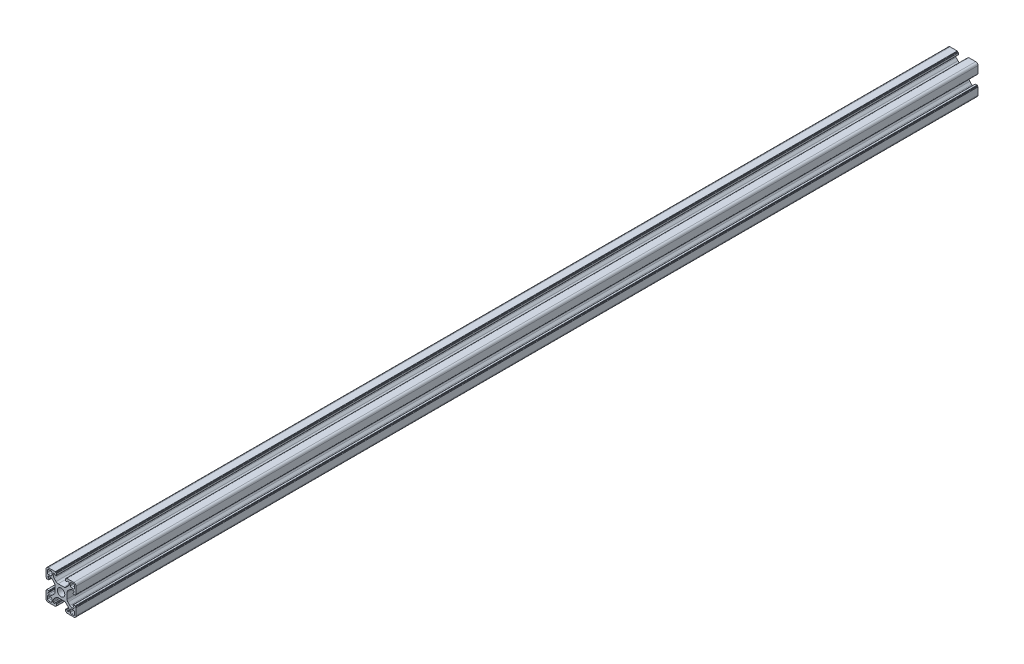
SolidWorks part; units mm, degrees
material "1060 Сплав"
ref_plane "Спереди" through (0, 0, 0) normal (0, 0, 1) x (1, 0, 0)
ref_plane "Сверху" through (0, 0, 0) normal (0, 1, 0) x (1, 0, 0)
ref_plane "Справа" through (0, 0, 0) normal (1, 0, 0) x (0, 0, -1)
sketch "Эскиз1" plane through (0, 0, 0) normal (0, 0, 1) x (1, 0, 0)
  line L0 (-22.0052, 70.3096) -> (-25.0052, 67.3096) construction
  line L1 (-31.1052, 65.2096) -> (-29.2064, 65.2096)
  line L2 (-31.1052, 61.2096) -> (-21.1052, 71.2096) construction
  line L3 (-23.5052, 68.8096) -> (-25.0052, 70.3096) construction
  line L4 (-27.7922, 65.7954) -> (-26.4909, 67.0967)
  line L5 (-24.2052, 67.3096) -> (-22.8052, 67.3096)
  line L6 (-25.0052, 68.1096) -> (-25.0052, 69.5096)
  line L7 (-22.8052, 70.3096) -> (-24.2052, 70.3096)
  line L8 (-25.9052, 69.4096) -> (-25.9052, 68.5109)
  line L9 (-27.3419, 69.2829) -> (-26.8616, 69.7632)
  line L10 (-27.9052, 70.7587) -> (-27.4052, 70.7587)
  line L11 (-27.5187, 69.2096) -> (-27.8052, 69.2096)
  line L12 (-26.508, 69.9096) -> (-26.4052, 69.9096)
  line L13 (-27.4052, 71.0596) -> (-27.4052, 70.7587)
  line L14 (-28.0552, 70.6087) -> (-28.0552, 69.4596)
  line L15 (-22.6052, 71.2096) -> (-27.2552, 71.2096)
  line L16 (-22.0052, 69.5096) -> (-22.0052, 68.1096)
  line L17 (-21.1052, 69.7096) -> (-21.1052, 65.0596)
  line L18 (-21.7061, 64.2596) -> (-22.8552, 64.2596)
  line L19 (-21.2552, 64.9096) -> (-21.5561, 64.9096)
  line L20 (-22.4052, 65.8068) -> (-22.4052, 65.9096)
  line L21 (-23.1052, 64.7961) -> (-23.1052, 64.5096)
  line L22 (-21.5561, 64.4096) -> (-21.5561, 64.9096)
  line L23 (-23.0319, 64.9729) -> (-22.5516, 65.4532)
  line L24 (-22.9052, 66.4096) -> (-23.8039, 66.4096)
  line L25 (-26.5194, 64.5226) -> (-25.2181, 65.8239)
  line L26 (-27.1052, 61.2096) -> (-27.1052, 63.1084)
  line L27 (-27.1052, 61.2096) -> (-27.1052, 59.3109)
  line L28 (-26.5194, 57.8967) -> (-25.2181, 56.5954)
  line L29 (-25.0052, 54.3096) -> (-25.0052, 52.9096)
  line L30 (-24.2052, 55.1096) -> (-22.8052, 55.1096)
  line L31 (-22.0052, 52.9096) -> (-22.0052, 54.3096)
  line L32 (-22.9052, 56.0096) -> (-23.8039, 56.0096)
  line L33 (-23.0319, 57.4464) -> (-22.5516, 56.9661)
  line L34 (-21.5561, 58.0096) -> (-21.5561, 57.5096)
  line L35 (-23.1052, 57.6232) -> (-23.1052, 57.9096)
  line L36 (-22.4052, 56.6125) -> (-22.4052, 56.5096)
  line L37 (-21.2552, 57.5096) -> (-21.5561, 57.5096)
  line L38 (-21.7061, 58.1596) -> (-22.8552, 58.1596)
  line L39 (-21.1052, 52.7096) -> (-21.1052, 57.3596)
  line L40 (-22.8052, 52.1096) -> (-24.2052, 52.1096)
  line L41 (-22.6052, 51.2096) -> (-27.2552, 51.2096)
  line L42 (-28.0552, 51.8106) -> (-28.0552, 52.9596)
  line L43 (-27.4052, 51.3596) -> (-27.4052, 51.6606)
  line L44 (-26.508, 52.5096) -> (-26.4052, 52.5096)
  line L45 (-27.5187, 53.2096) -> (-27.8052, 53.2096)
  line L46 (-27.9052, 51.6606) -> (-27.4052, 51.6606)
  line L47 (-27.3419, 53.1364) -> (-26.8616, 52.6561)
  line L48 (-25.9052, 53.0096) -> (-25.9052, 53.9084)
  line L49 (-27.7922, 56.6239) -> (-26.4909, 55.3226)
  line L50 (-31.1052, 57.2096) -> (-29.2064, 57.2096)
  line L51 (-22.0052, 52.1096) -> (-25.0052, 55.1096) construction
  line L52 (-31.1052, 61.2096) -> (-21.1052, 51.2096) construction
  line L53 (-23.5052, 53.6096) -> (-22.0052, 55.1096) construction
  line L54 (-31.1052, 57.2096) -> (-33.0039, 57.2096)
  line L55 (-34.4181, 56.6239) -> (-35.7194, 55.3226)
  line L56 (-38.0052, 55.1096) -> (-39.4052, 55.1096)
  line L57 (-37.2052, 54.3096) -> (-37.2052, 52.9096)
  line L58 (-39.4052, 52.1096) -> (-38.0052, 52.1096)
  line L59 (-36.3052, 53.0096) -> (-36.3052, 53.9084)
  line L60 (-34.8684, 53.1364) -> (-35.3487, 52.6561)
  line L61 (-34.3052, 51.6606) -> (-34.8052, 51.6606)
  line L62 (-34.6916, 53.2096) -> (-34.4052, 53.2096)
  line L63 (-35.7023, 52.5096) -> (-35.8052, 52.5096)
  line L64 (-34.8052, 51.3596) -> (-34.8052, 51.6606)
  line L65 (-34.1552, 51.8106) -> (-34.1552, 52.9596)
  line L66 (-39.6052, 51.2096) -> (-34.9552, 51.2096)
  line L67 (-40.2052, 52.9096) -> (-40.2052, 54.3096)
  line L68 (-41.1052, 52.7096) -> (-41.1052, 57.3596)
  line L69 (-40.5042, 58.1596) -> (-39.3552, 58.1596)
  line L70 (-40.9552, 57.5096) -> (-40.6542, 57.5096)
  line L71 (-39.8052, 56.6125) -> (-39.8052, 56.5096)
  line L72 (-39.1052, 57.6232) -> (-39.1052, 57.9096)
  line L73 (-40.6542, 58.0096) -> (-40.6542, 57.5096)
  line L74 (-39.1784, 57.4464) -> (-39.6587, 56.9661)
  line L75 (-39.3052, 56.0096) -> (-38.4064, 56.0096)
  line L76 (-35.6909, 57.8967) -> (-36.9922, 56.5954)
  line L77 (-35.1052, 61.2096) -> (-35.1052, 59.3109)
  line L78 (-40.2052, 52.1096) -> (-37.2052, 55.1096) construction
  line L79 (-31.1052, 61.2096) -> (-41.1052, 51.2096) construction
  line L80 (-38.7052, 53.6096) -> (-37.2052, 52.1096) construction
  line L81 (-35.1052, 61.2096) -> (-35.1052, 63.1084)
  line L82 (-35.6909, 64.5226) -> (-36.9922, 65.8239)
  line L83 (-37.2052, 68.1096) -> (-37.2052, 69.5096)
  line L84 (-38.0052, 67.3096) -> (-39.4052, 67.3096)
  line L85 (-40.2052, 69.5096) -> (-40.2052, 68.1096)
  line L86 (-39.3052, 66.4096) -> (-38.4064, 66.4096)
  line L87 (-39.1784, 64.9729) -> (-39.6587, 65.4532)
  line L88 (-40.6542, 64.4096) -> (-40.6542, 64.9096)
  line L89 (-39.1052, 64.7961) -> (-39.1052, 64.5096)
  line L90 (-39.8052, 65.8068) -> (-39.8052, 65.9096)
  line L91 (-40.9552, 64.9096) -> (-40.6542, 64.9096)
  line L92 (-40.5042, 64.2596) -> (-39.3552, 64.2596)
  line L93 (-41.1052, 69.7096) -> (-41.1052, 65.0596)
  line L94 (-39.4052, 70.3096) -> (-38.0052, 70.3096)
  line L95 (-39.6052, 71.2096) -> (-34.9552, 71.2096)
  line L96 (-34.1552, 70.6087) -> (-34.1552, 69.4596)
  line L97 (-34.8052, 71.0596) -> (-34.8052, 70.7587)
  line L98 (-35.7023, 69.9096) -> (-35.8052, 69.9096)
  line L99 (-34.6916, 69.2096) -> (-34.4052, 69.2096)
  line L100 (-34.3052, 70.7587) -> (-34.8052, 70.7587)
  line L101 (-34.8684, 69.2829) -> (-35.3487, 69.7632)
  line L102 (-36.3052, 69.4096) -> (-36.3052, 68.5109)
  line L103 (-34.4181, 65.7954) -> (-35.7194, 67.0967)
  line L104 (-31.1052, 65.2096) -> (-33.0039, 65.2096)
  line L105 (-42.8692, 61.2096) -> (-19.6008, 61.2096) construction
  line L106 (-40.2052, 70.3096) -> (-37.2052, 67.3096) construction
  line L107 (-31.1052, 49.1232) -> (-31.1052, 71.9286) construction
  line L108 (-31.1052, 61.2096) -> (-41.1052, 71.2096) construction
  line L109 (-38.7052, 68.8096) -> (-40.2052, 67.3096) construction
  arc A0 (-22.0052, 69.5096) -> (-22.8052, 70.3096) centre (-22.8052, 69.5096) ccw
  arc A1 (-24.2052, 70.3096) -> (-25.0052, 69.5096) centre (-24.2052, 69.5096) ccw
  arc A2 (-24.2052, 67.3096) -> (-25.0052, 68.1096) centre (-24.2052, 68.1096) cw
  arc A3 (-22.6052, 71.2096) -> (-21.1052, 69.7096) centre (-22.6052, 69.7096) cw
  arc A4 (-27.9052, 70.7587) -> (-28.0552, 70.6087) centre (-27.9052, 70.6087) ccw
  arc A5 (-27.2552, 71.2096) -> (-27.4052, 71.0596) centre (-27.2552, 71.0596) ccw
  arc A6 (-27.5187, 69.2096) -> (-27.3419, 69.2829) centre (-27.5187, 69.4596) ccw
  arc A7 (-27.8052, 69.2096) -> (-28.0552, 69.4596) centre (-27.8052, 69.4596) cw
  arc A8 (-26.8616, 69.7632) -> (-26.508, 69.9096) centre (-26.508, 69.4096) cw
  arc A9 (-26.4052, 69.9096) -> (-25.9052, 69.4096) centre (-26.4052, 69.4096) cw
  arc A10 (-28.6052, 61.2096) -> (-31.1052, 63.7096) centre (-31.1052, 61.2096) ccw
  arc A11 (-29.2064, 65.2096) -> (-27.7922, 65.7954) centre (-29.2064, 67.2096) ccw
  arc A12 (-25.9052, 68.5109) -> (-26.4909, 67.0967) centre (-27.9052, 68.5109) cw
  arc A13 (-22.0052, 68.1096) -> (-22.8052, 67.3096) centre (-22.8052, 68.1096) cw
  arc A14 (-22.4052, 65.9096) -> (-22.9052, 66.4096) centre (-22.9052, 65.9096) ccw
  arc A15 (-22.5516, 65.4532) -> (-22.4052, 65.8068) centre (-22.9052, 65.8068) ccw
  arc A16 (-23.1052, 64.5096) -> (-22.8552, 64.2596) centre (-22.8552, 64.5096) ccw
  arc A17 (-23.1052, 64.7961) -> (-23.0319, 64.9729) centre (-22.8552, 64.7961) cw
  arc A18 (-21.1052, 65.0596) -> (-21.2552, 64.9096) centre (-21.2552, 65.0596) cw
  arc A19 (-21.5561, 64.4096) -> (-21.7061, 64.2596) centre (-21.7061, 64.4096) cw
  arc A20 (-23.8039, 66.4096) -> (-25.2181, 65.8239) centre (-23.8039, 64.4096) ccw
  arc A21 (-27.1052, 63.1084) -> (-26.5194, 64.5226) centre (-25.1052, 63.1084) cw
  arc A22 (-22.8052, 52.1096) -> (-22.0052, 52.9096) centre (-22.8052, 52.9096) ccw
  arc A23 (-22.0052, 54.3096) -> (-22.8052, 55.1096) centre (-22.8052, 54.3096) ccw
  arc A24 (-25.0052, 54.3096) -> (-24.2052, 55.1096) centre (-24.2052, 54.3096) cw
  arc A25 (-21.1052, 52.7096) -> (-22.6052, 51.2096) centre (-22.6052, 52.7096) cw
  arc A26 (-21.5561, 58.0096) -> (-21.7061, 58.1596) centre (-21.7061, 58.0096) ccw
  arc A27 (-21.1052, 57.3596) -> (-21.2552, 57.5096) centre (-21.2552, 57.3596) ccw
  arc A28 (-23.1052, 57.6232) -> (-23.0319, 57.4464) centre (-22.8552, 57.6232) ccw
  arc A29 (-23.1052, 57.9096) -> (-22.8552, 58.1596) centre (-22.8552, 57.9096) cw
  arc A30 (-22.5516, 56.9661) -> (-22.4052, 56.6125) centre (-22.9052, 56.6125) cw
  arc A31 (-22.4052, 56.5096) -> (-22.9052, 56.0096) centre (-22.9052, 56.5096) cw
  arc A32 (-31.1052, 58.7096) -> (-28.6052, 61.2096) centre (-31.1052, 61.2096) ccw
  arc A33 (-27.1052, 59.3109) -> (-26.5194, 57.8967) centre (-25.1052, 59.3109) ccw
  arc A34 (-23.8039, 56.0096) -> (-25.2181, 56.5954) centre (-23.8039, 58.0096) cw
  arc A35 (-24.2052, 52.1096) -> (-25.0052, 52.9096) centre (-24.2052, 52.9096) cw
  arc A36 (-26.4052, 52.5096) -> (-25.9052, 53.0096) centre (-26.4052, 53.0096) ccw
  arc A37 (-26.8616, 52.6561) -> (-26.508, 52.5096) centre (-26.508, 53.0096) ccw
  arc A38 (-27.8052, 53.2096) -> (-28.0552, 52.9596) centre (-27.8052, 52.9596) ccw
  arc A39 (-27.5187, 53.2096) -> (-27.3419, 53.1364) centre (-27.5187, 52.9596) cw
  arc A40 (-27.2552, 51.2096) -> (-27.4052, 51.3596) centre (-27.2552, 51.3596) cw
  arc A41 (-27.9052, 51.6606) -> (-28.0552, 51.8106) centre (-27.9052, 51.8106) cw
  arc A42 (-25.9052, 53.9084) -> (-26.4909, 55.3226) centre (-27.9052, 53.9084) ccw
  arc A43 (-29.2064, 57.2096) -> (-27.7922, 56.6239) centre (-29.2064, 55.2096) cw
  arc A44 (-40.2052, 52.9096) -> (-39.4052, 52.1096) centre (-39.4052, 52.9096) ccw
  arc A45 (-38.0052, 52.1096) -> (-37.2052, 52.9096) centre (-38.0052, 52.9096) ccw
  arc A46 (-38.0052, 55.1096) -> (-37.2052, 54.3096) centre (-38.0052, 54.3096) cw
  arc A47 (-39.6052, 51.2096) -> (-41.1052, 52.7096) centre (-39.6052, 52.7096) cw
  arc A48 (-34.3052, 51.6606) -> (-34.1552, 51.8106) centre (-34.3052, 51.8106) ccw
  arc A49 (-34.9552, 51.2096) -> (-34.8052, 51.3596) centre (-34.9552, 51.3596) ccw
  arc A50 (-34.6916, 53.2096) -> (-34.8684, 53.1364) centre (-34.6916, 52.9596) ccw
  arc A51 (-34.4052, 53.2096) -> (-34.1552, 52.9596) centre (-34.4052, 52.9596) cw
  arc A52 (-35.3487, 52.6561) -> (-35.7023, 52.5096) centre (-35.7023, 53.0096) cw
  arc A53 (-35.8052, 52.5096) -> (-36.3052, 53.0096) centre (-35.8052, 53.0096) cw
  arc A54 (-33.6052, 61.2096) -> (-31.1052, 58.7096) centre (-31.1052, 61.2096) ccw
  arc A55 (-33.0039, 57.2096) -> (-34.4181, 56.6239) centre (-33.0039, 55.2096) ccw
  arc A56 (-36.3052, 53.9084) -> (-35.7194, 55.3226) centre (-34.3052, 53.9084) cw
  arc A57 (-40.2052, 54.3096) -> (-39.4052, 55.1096) centre (-39.4052, 54.3096) cw
  arc A58 (-39.8052, 56.5096) -> (-39.3052, 56.0096) centre (-39.3052, 56.5096) ccw
  arc A59 (-39.6587, 56.9661) -> (-39.8052, 56.6125) centre (-39.3052, 56.6125) ccw
  arc A60 (-39.1052, 57.9096) -> (-39.3552, 58.1596) centre (-39.3552, 57.9096) ccw
  arc A61 (-39.1052, 57.6232) -> (-39.1784, 57.4464) centre (-39.3552, 57.6232) cw
  arc A62 (-41.1052, 57.3596) -> (-40.9552, 57.5096) centre (-40.9552, 57.3596) cw
  arc A63 (-40.6542, 58.0096) -> (-40.5042, 58.1596) centre (-40.5042, 58.0096) cw
  arc A64 (-38.4064, 56.0096) -> (-36.9922, 56.5954) centre (-38.4064, 58.0096) ccw
  arc A65 (-35.1052, 59.3109) -> (-35.6909, 57.8967) centre (-37.1052, 59.3109) cw
  arc A66 (-39.4052, 70.3096) -> (-40.2052, 69.5096) centre (-39.4052, 69.5096) ccw
  arc A67 (-40.2052, 68.1096) -> (-39.4052, 67.3096) centre (-39.4052, 68.1096) ccw
  arc A68 (-37.2052, 68.1096) -> (-38.0052, 67.3096) centre (-38.0052, 68.1096) cw
  arc A69 (-41.1052, 69.7096) -> (-39.6052, 71.2096) centre (-39.6052, 69.7096) cw
  arc A70 (-40.6542, 64.4096) -> (-40.5042, 64.2596) centre (-40.5042, 64.4096) ccw
  arc A71 (-41.1052, 65.0596) -> (-40.9552, 64.9096) centre (-40.9552, 65.0596) ccw
  arc A72 (-39.1052, 64.7961) -> (-39.1784, 64.9729) centre (-39.3552, 64.7961) ccw
  arc A73 (-39.1052, 64.5096) -> (-39.3552, 64.2596) centre (-39.3552, 64.5096) cw
  arc A74 (-39.6587, 65.4532) -> (-39.8052, 65.8068) centre (-39.3052, 65.8068) cw
  arc A75 (-39.8052, 65.9096) -> (-39.3052, 66.4096) centre (-39.3052, 65.9096) cw
  arc A76 (-31.1052, 63.7096) -> (-33.6052, 61.2096) centre (-31.1052, 61.2096) ccw
  arc A77 (-35.1052, 63.1084) -> (-35.6909, 64.5226) centre (-37.1052, 63.1084) ccw
  arc A78 (-38.4064, 66.4096) -> (-36.9922, 65.8239) centre (-38.4064, 64.4096) cw
  arc A79 (-38.0052, 70.3096) -> (-37.2052, 69.5096) centre (-38.0052, 69.5096) cw
  arc A80 (-35.8052, 69.9096) -> (-36.3052, 69.4096) centre (-35.8052, 69.4096) ccw
  arc A81 (-35.3487, 69.7632) -> (-35.7023, 69.9096) centre (-35.7023, 69.4096) ccw
  arc A82 (-34.4052, 69.2096) -> (-34.1552, 69.4596) centre (-34.4052, 69.4596) ccw
  arc A83 (-34.6916, 69.2096) -> (-34.8684, 69.2829) centre (-34.6916, 69.4596) cw
  arc A84 (-34.9552, 71.2096) -> (-34.8052, 71.0596) centre (-34.9552, 71.0596) cw
  arc A85 (-34.3052, 70.7587) -> (-34.1552, 70.6087) centre (-34.3052, 70.6087) cw
  arc A86 (-36.3052, 68.5109) -> (-35.7194, 67.0967) centre (-34.3052, 68.5109) ccw
  arc A87 (-33.0039, 65.2096) -> (-34.4181, 65.7954) centre (-33.0039, 67.2096) cw
  point P0 (-31.1052, 61.2096)
  point P9 (-31.1052, 61.2096)
  point P40 (-22.4052, 64.9096)
  point P93 (-27.4052, 52.5096)
  point P144 (-27.4052, 69.9096)
  point P152 (-22.4052, 57.5096)
  point P153 (-31.1052, 57.2854)
  point P154 (-31.1052, 61.2096)
  point P189 (-39.8052, 57.5096)
  point P228 (-34.8052, 52.5096)
  point P229 (-35.0294, 61.2096)
  point P230 (-31.1052, 61.2096)
  point P268 (-34.8052, 69.9096)
  point P273 (-27.1809, 61.2096)
  point P306 (-39.8052, 64.9096)
  point P307 (-31.1052, 65.1339)
  point P309 (-31.1052, 61.2096)
  dimension "D3" = 5
  dimension "D6" = 2
  dimension "D1" = 2
  dimension "D2" = 6
  dimension "D4" = 4
  dimension "D5" = 0.9
extrude "Бобышка-Вытянуть1" add sketch "Эскиз1" along normal blind 600
